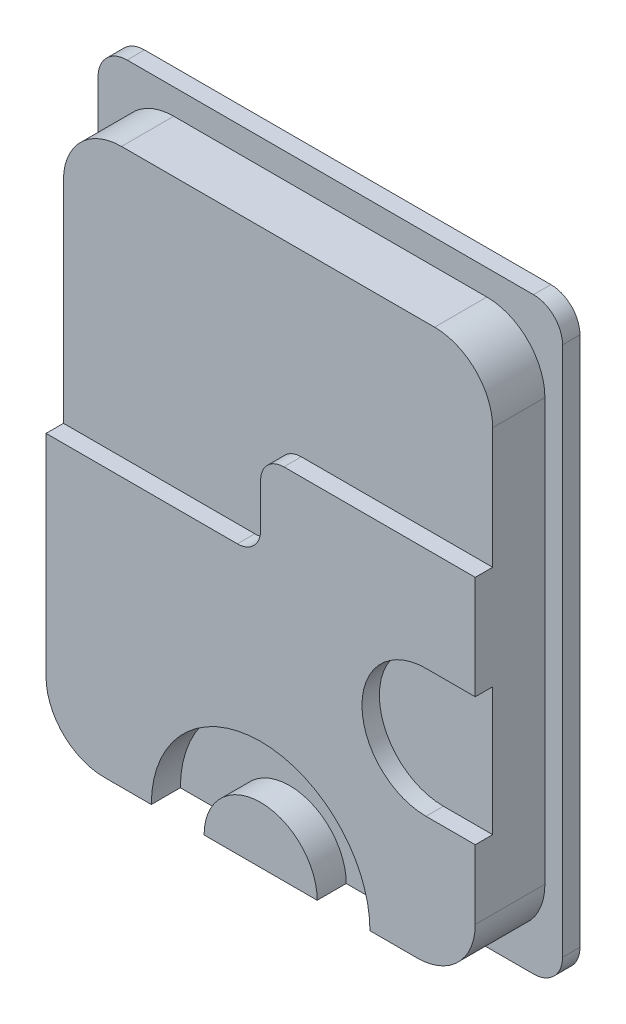
SolidWorks part; units mm, degrees
material "6061 Alloy"
ref_plane "Front Plane" through (0, 0, 0) normal (0, 0, 1) x (1, 0, 0)
ref_plane "Top Plane" through (0, 0, 0) normal (0, 1, 0) x (1, 0, 0)
ref_plane "Right Plane" through (0, 0, 0) normal (1, 0, 0) x (0, 0, -1)
sketch "Sketch1" plane through (0, 0, 0) normal (0, 0, 1) x (1, 0, 0)
  line L13 (5, 0) -> (75, 0)
  line L14 (0, 5) -> (0, 96.346)
  line L15 (5, 101.346) -> (75, 101.346)
  line L16 (80, 5) -> (80, 96.346)
  arc A0 (5, 0) -> (0, 5) centre (5, 5) cw
  arc A1 (75, 0) -> (80, 5) centre (75, 5) ccw
  arc A2 (75, 101.346) -> (80, 96.346) centre (75, 96.346) cw
  arc A3 (0, 96.346) -> (5, 101.346) centre (5, 96.346) cw
  point P7 (0, 0)
  point P9 (0, 0)
  dimension "D1" = 5
extrude "Boss-Extrude1" add sketch "Sketch1" along normal blind 15
ref_point "Point1"
sketch "Sketch3" plane through (0, 0, 15) normal (0, 0, 1) x (1, 0, 0)
  line L1 (13.037, 4.3718) -> (66.963, 4.3718)
  line L2 (3.037, 14.3718) -> (3.037, 86.9742)
  line L3 (13.037, 96.9742) -> (66.963, 96.9742)
  line L4 (76.963, 14.3718) -> (76.963, 86.9742)
  line L5 (3.037, 4.3718) -> (76.963, 96.9742) construction
  line L6 (3.037, 96.9742) -> (76.963, 4.3718) construction
  line L7 (-12.212, -10.0064) -> (92.212, -10.0064)
  line L8 (-12.212, -10.0064) -> (-12.212, 111.3524)
  line L9 (-12.212, 111.3524) -> (92.212, 111.3524)
  line L10 (92.212, -10.0064) -> (92.212, 111.3524)
  line L11 (-12.212, -10.0064) -> (92.212, 111.3524) construction
  line L12 (-12.212, 111.3524) -> (92.212, -10.0064) construction
  arc A0 (13.037, 4.3718) -> (3.037, 14.3718) centre (13.037, 14.3718) cw
  arc A1 (66.963, 4.3718) -> (76.963, 14.3718) centre (66.963, 14.3718) ccw
  arc A2 (66.963, 96.9742) -> (76.963, 86.9742) centre (66.963, 86.9742) cw
  arc A3 (3.037, 86.9742) -> (13.037, 96.9742) centre (13.037, 86.9742) cw
  point P0 (40, 50.673)
  point P6 (40, 50.673)
  dimension "D1" = 10
extrude "Cut-Extrude1" cut sketch "Sketch3" against normal blind 12
sketch "Sketch4" plane through (0, 0, 15) normal (0, 0, 1) x (1, 0, 0)
  line L0 (36, 50.673) -> (3.037, 50.673)
  line L1 (3.037, 86.9742) -> (3.037, 14.3718) construction
  line L2 (40, 54.673) -> (40, 62.1591)
  line L3 (44, 66.1591) -> (76.963, 66.1591)
  line L4 (76.963, 14.3718) -> (76.963, 86.9742) construction
  line L5 (3.037, 50.673) -> (3.037, 113.1352)
  line L6 (3.037, 113.1352) -> (76.963, 113.1352)
  line L7 (76.963, 113.1352) -> (76.963, 66.1591)
  arc A0 (40, 62.1591) -> (44, 66.1591) centre (44, 62.1591) cw
  arc A1 (36, 50.673) -> (40, 54.673) centre (36, 54.673) ccw
  point P13 (40, 50.673)
  dimension "D1" = 4
  dimension "D2" = 4
extrude "Cut-Extrude2" cut sketch "Sketch4" against normal blind 3
sketch "Sketch5" plane through (0, 0, 15) normal (0, 0, 1) x (1, 0, 0)
  line L0 (83.7106, 37.3053) -> (68.4819, 37.3053) construction
  line L1 (83.7106, 26.2747) -> (68.4819, 26.2747)
  line L2 (83.7106, 48.3359) -> (68.4819, 48.3359)
  arc A0 (83.7106, 26.2747) -> (83.7106, 48.3359) centre (83.7106, 37.3053) ccw
  arc A1 (68.4819, 48.3359) -> (68.4819, 26.2747) centre (68.4819, 37.3053) ccw
  point P2 (76.0963, 37.3053)
extrude "Cut-Extrude3" cut sketch "Sketch5" against normal blind 3
sketch "Sketch6" plane through (0, 0, 15) normal (0, 0, 1) x (1, 0, 0)
  line L0 (13.037, 4.3718) -> (66.963, 4.3718) construction
  circle A0 centre (40, 4.3718) radius 18.8281
  circle A1 centre (40, 4.3718) radius 9.7394
extrude "Cut-Extrude4" cut sketch "Sketch6" against normal blind 5
